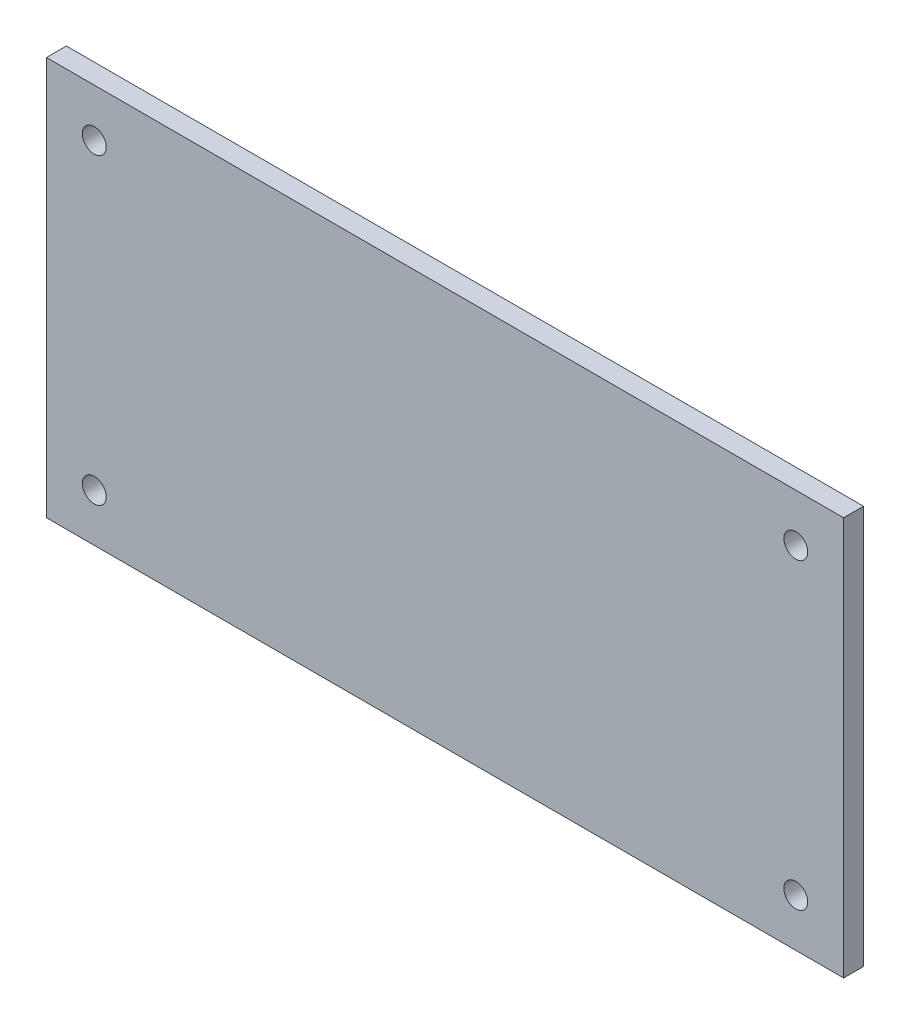
SolidWorks part; units mm, degrees
ref_plane "前视基准面" through (0, 0, 0) normal (0, 0, 1) x (1, 0, 0)
ref_plane "上视基准面" through (0, 0, 0) normal (0, 1, 0) x (1, 0, 0)
ref_plane "右视基准面" through (0, 0, 0) normal (1, 0, 0) x (0, 0, -1)
other "Configuration Table"
sketch "草图1" plane through (0, 0, 0) normal (0, 0, 1) x (1, 0, 0)
  line L1 (-1000, -500) -> (1000, -500)
  line L2 (-1000, -500) -> (-1000, 500)
  line L3 (-1000, 500) -> (1000, 500)
  line L4 (1000, -500) -> (1000, 500)
  line L5 (-1000, -500) -> (1000, 500) construction
  line L6 (-1000, 500) -> (1000, -500) construction
  point P0 (0, 0)
extrude "凸台-拉伸1" add sketch "草图1" along normal blind 50
sketch "草图2" plane through (0, 0, 0) normal (0, 0, 1) x (1, 0, 0)
  circle A0 centre (880, 380) radius 30
extrude "切除-拉伸1" cut sketch "草图2" along normal through all
sketch "草图3" plane through (0, 0, 0) normal (0, 0, 1) x (1, 0, 0)
  circle A0 centre (880, -380) radius 30
extrude "切除-拉伸2" cut sketch "草图3" along normal through all
sketch "草图4" plane through (0, 0, 0) normal (0, 0, 1) x (1, 0, 0)
  circle A0 centre (-880, 380) radius 30
extrude "切除-拉伸3" cut sketch "草图4" along normal through all
sketch "草图5" plane through (0, 0, 0) normal (0, 0, 1) x (1, 0, 0)
  circle A0 centre (-880, -380) radius 30
extrude "切除-拉伸4" cut sketch "草图5" along normal through all
